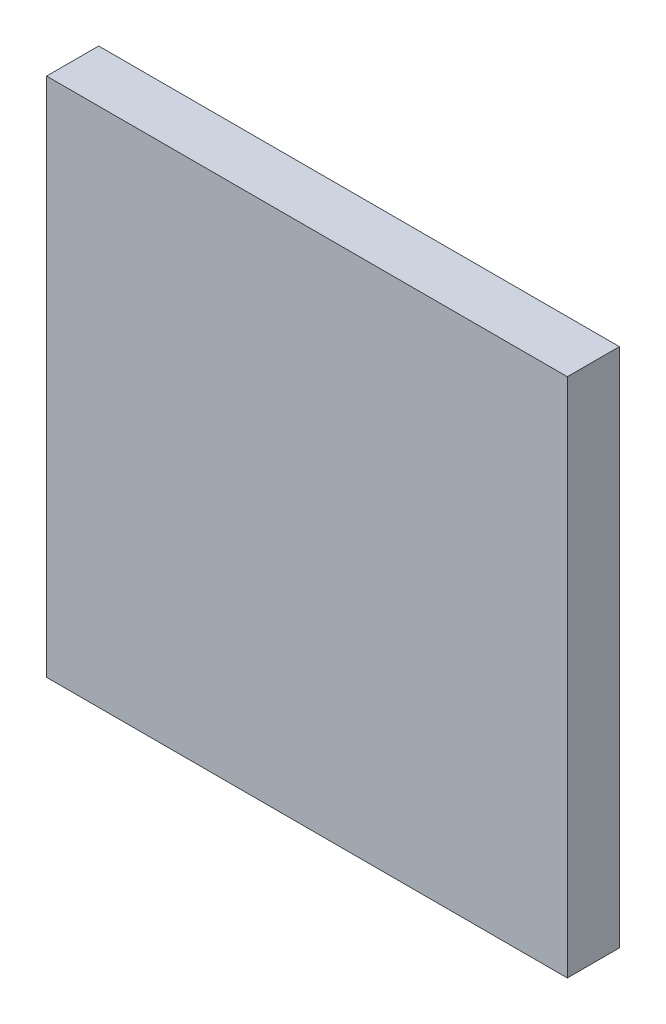
SolidWorks part; units mm, degrees
ref_plane "前视基准面" through (0, 0, 0) normal (0, 0, 1) x (1, 0, 0)
ref_plane "上视基准面" through (0, 0, 0) normal (0, 1, 0) x (1, 0, 0)
ref_plane "右视基准面" through (0, 0, 0) normal (1, 0, 0) x (0, 0, -1)
sketch "草图1" plane through (0, 0, 0) normal (0, 0, 1) x (1, 0, 0)
  line L1 (-100, 100) -> (100, 100)
  line L2 (-100, 100) -> (-100, -100)
  line L3 (-100, -100) -> (100, -100)
  line L4 (100, 100) -> (100, -100)
  line L5 (-100, 100) -> (100, -100) construction
  line L6 (-100, -100) -> (100, 100) construction
  point P0 (0, 0)
  dimension "D1" = 200
  dimension "D2" = 200
extrude "凸台-拉伸1" add sketch "草图1" along normal mid plane 20
equation "\"零件重量\"= \"SW-质量\""
